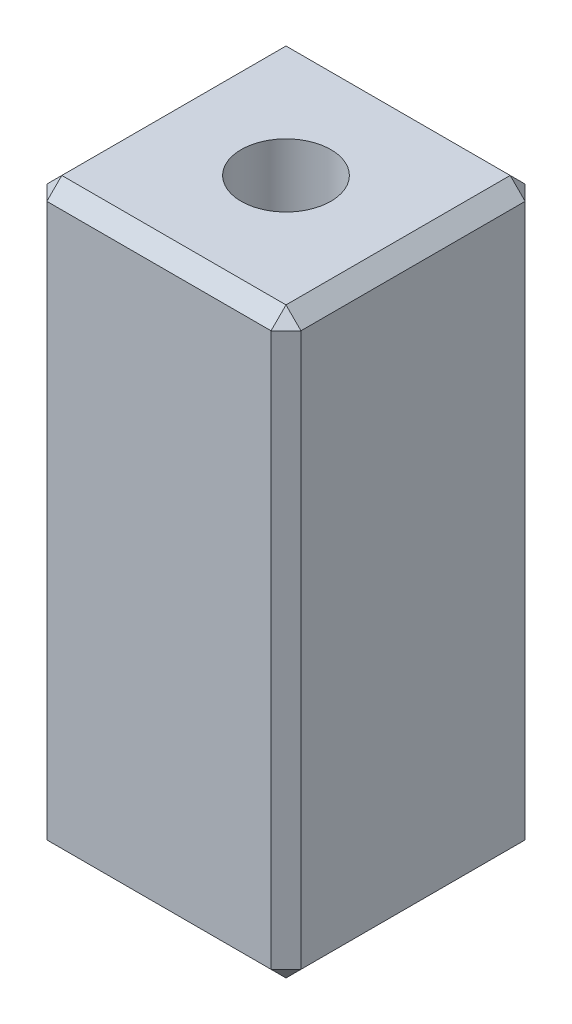
SolidWorks part; units mm, degrees
ref_plane "Front Plane" through (0, 0, 0) normal (0, 0, 1) x (1, 0, 0)
ref_plane "Top Plane" through (0, 0, 0) normal (0, 1, 0) x (1, 0, 0)
ref_plane "Right Plane" through (0, 0, 0) normal (1, 0, 0) x (0, 0, -1)
sketch "Sketch1" plane through (0, 0, 0) normal (0, 1, 0) x (1, 0, 0)
  line L1 (-4.25, 4.25) -> (4.25, 4.25)
  line L2 (-4.25, 4.25) -> (-4.25, -4.25)
  line L3 (-4.25, -4.25) -> (4.25, -4.25)
  line L4 (4.25, 4.25) -> (4.25, -4.25)
  line L5 (-4.25, 4.25) -> (4.25, -4.25) construction
  line L6 (-4.25, -4.25) -> (4.25, 4.25) construction
  circle A0 centre (0, 0) radius 1.5
  point P0 (0, 0)
  dimension "D3" = 3
  dimension "D1" = 8.5
  dimension "D2" = 8.5
extrude "Boss-Extrude1" add sketch "Sketch1" along normal blind 19.5
chamfer "Chamfer1" distance 0.5 angle 45 12 edges at (-4.25, 0, 0) (0, 0, -4.25) (-4.25, 9.75, -4.25) (4.25, 0, 0) (0, 0, 4.25) (-4.25, 9.75, 4.25) (-4.25, 19.5, 0) (4.25, 9.75, -4.25) (0, 19.5, -4.25) (4.25, 19.5, 0) (4.25, 9.75, 4.25) (0, 19.5, 4.25)
